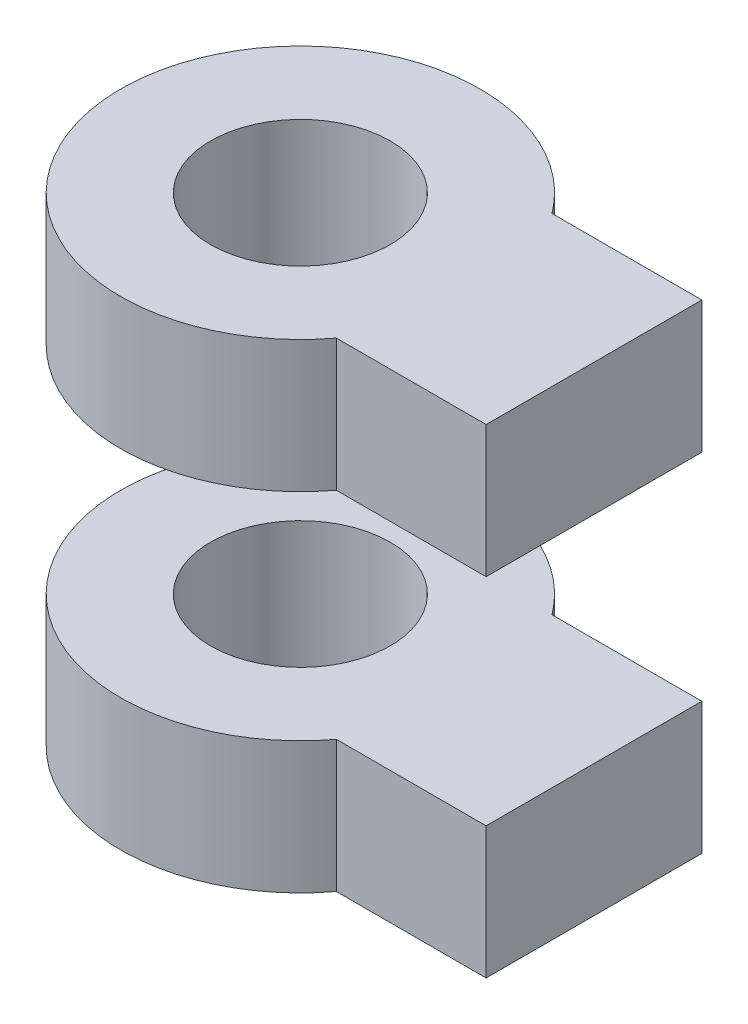
SolidWorks part; units mm, degrees
ref_plane "Front Plane" through (0, 0, 0) normal (0, 0, 1) x (1, 0, 0)
ref_plane "Top Plane" through (0, 0, 0) normal (0, 1, 0) x (1, 0, 0)
ref_plane "Right Plane" through (0, 0, 0) normal (1, 0, 0) x (0, 0, -1)
sketch "Croquis3" plane through (0, 0, 0) normal (0, 1, 0) x (1, 0, 0)
  line L1 (24, -18) -> (49, -18)
  line L3 (24, 18) -> (49, 18)
  line L4 (49, -18) -> (49, 18)
  line L5 (30, 0) -> (49, 18) construction
  line L6 (30, 0) -> (49, -18) construction
  arc A0 (24, 18) -> (24, -18) centre (0, 0) ccw
  circle A1 centre (0, 0) radius 15
  point P3 (30, 0)
  dimension "D1" = 60
  dimension "D2" = 30
  dimension "D4" = 36
extrude "Saliente-Extruir3" add sketch "Croquis3" along normal mid plane 80
sketch "Croquis6" plane through (0, 0, 0) normal (0, 0, 1) x (1, 0, 0)
  line L0 (15, 40) -> (-15, 40) construction
  line L1 (-34.1435, 18) -> (56.9863, 18)
  line L2 (-34.1435, 18) -> (-34.1435, -18)
  line L3 (-34.1435, -18) -> (56.9863, -18)
  line L4 (56.9863, 18) -> (56.9863, -18)
  dimension "D1" = 22
  dimension "D2" = 36
extrude "Cortar-Extruir2" cut sketch "Croquis6" against normal mid plane 80
sketch "Croquis7" plane through (0, 0, 18) normal (0, 0, 1) x (1, 0, 0)
  line L0 (49, 40) -> (49, 18)
  line L1 (49, -18) -> (49, -40)
  arc A0 (49, 18) -> (49, -18) centre (49, 0) cw
  arc A1 (49, 40) -> (49, -40) centre (49, 0) cw
